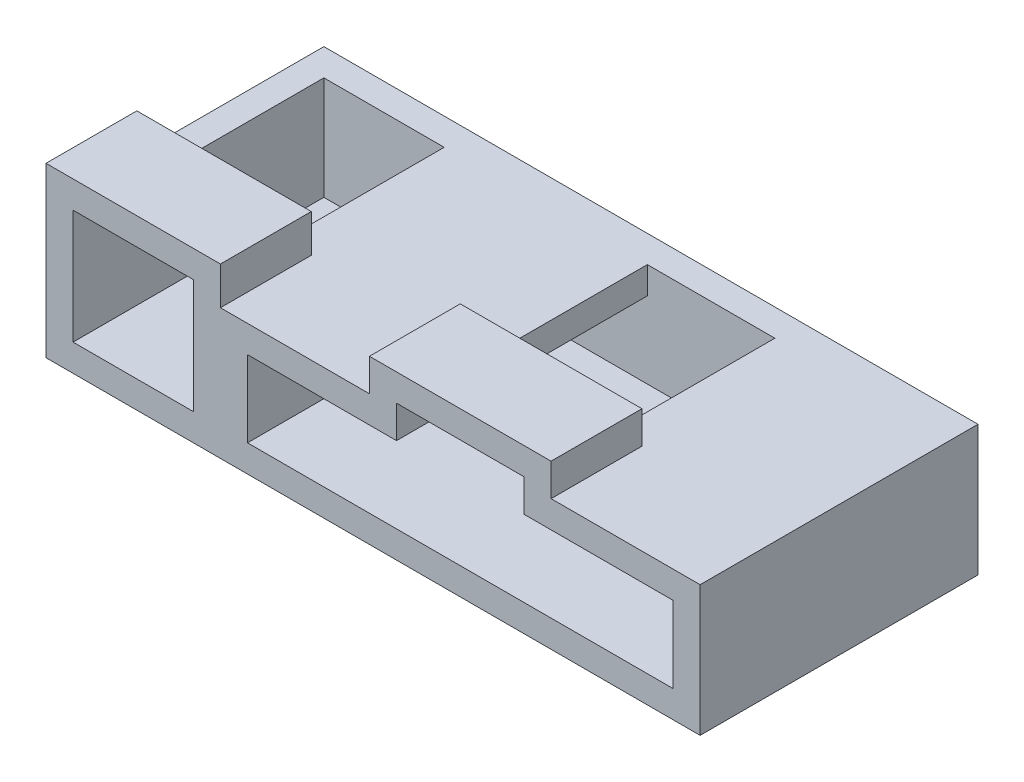
SolidWorks part; units mm, degrees
ref_plane "Front Plane" through (0, 0, 0) normal (0, 0, 1) x (1, 0, 0)
ref_plane "Top Plane" through (0, 0, 0) normal (0, 1, 0) x (1, 0, 0)
ref_plane "Right Plane" through (0, 0, 0) normal (1, 0, 0) x (0, 0, -1)
sketch "Sketch1" plane through (0, 0, 0) normal (0, 1, 0) x (1, 0, 0)
  line L1 (-43.6495, 20.2828) -> (-16.027, 20.2828)
  line L2 (-43.6495, 20.2828) -> (-43.6495, 32.0176)
  line L3 (-43.6495, 32.0176) -> (-16.027, 32.0176)
  line L4 (-16.027, 20.2828) -> (-16.027, 32.0176)
  dimension "D1" = 27.6225
  dimension "D2" = 11.7348
extrude "Boss-Extrude1" add sketch "Sketch1" along normal blind 7.112
sketch "Sketch2" plane through (0, 0, -20.2828) normal (0, 0, 1) x (1, 0, 0)
  line L0 (-36.2835, 7.112) -> (-36.2835, 5.5118)
  line L1 (-43.6495, 7.112) -> (-16.027, 7.112) construction
  line L2 (-36.2835, 5.5118) -> (-29.9906, 5.5118)
  line L3 (-29.9906, 5.5118) -> (-29.9906, 6.8834)
  line L4 (-29.9906, 6.8834) -> (-22.3198, 6.8834)
  line L5 (-22.3198, 6.8834) -> (-22.3198, 5.5118)
  line L6 (-22.3198, 5.5118) -> (-16.027, 5.5118)
  line L7 (-16.027, 7.112) -> (-16.027, 0) construction
  line L8 (-43.6495, 7.112) -> (-43.6495, 0) construction
  dimension "D1" = 7.366
  dimension "D2" = 1.6002
  dimension "D3" = 7.6708
  dimension "D4" = 1.3716
extrude "Cut-Extrude1" cut sketch "Sketch2" along direction (0, 0, -1) on the side against the normal through all and the other way through all
sketch "Sketch3" plane through (0, 0, -20.2828) normal (0, 0, 1) x (1, 0, 0)
  line L0 (-43.6495, 7.112) -> (-36.2835, 7.112) construction
  line L1 (-36.2835, 7.112) -> (-36.2835, 0) construction
  line L2 (-43.6495, 0) -> (-16.027, 0) construction
  line L3 (-36.2835, 0) -> (-43.6495, 0) construction
  line L4 (-43.6495, 0) -> (-43.6495, 7.112) construction
  line L5 (-42.5065, 5.969) -> (-37.4265, 5.969)
  line L6 (-37.4265, 5.969) -> (-37.4265, 1.143)
  line L7 (-37.4265, 1.143) -> (-42.5065, 1.143)
  line L8 (-42.5065, 1.143) -> (-42.5065, 5.969)
  line L9 (-36.2835, 5.5118) -> (-36.2835, 0) construction
  line L10 (-36.2835, 0) -> (-16.027, 0) construction
  line L11 (-16.027, 0) -> (-16.027, 5.5118) construction
  line L12 (-22.3198, 5.5118) -> (-16.027, 5.5118) construction
  line L13 (-16.027, 5.5118) -> (-16.027, 0) construction
  line L14 (-16.027, 5.5118) -> (-22.3198, 5.5118) construction
  line L15 (-22.3198, 5.5118) -> (-22.3198, 6.8834) construction
  line L16 (-22.3198, 6.8834) -> (-29.9906, 6.8834) construction
  line L17 (-29.9906, 6.8834) -> (-29.9906, 5.5118) construction
  line L18 (-29.9906, 5.5118) -> (-36.2835, 5.5118) construction
  line L19 (-35.1405, 4.3688) -> (-35.1405, 1.143)
  line L20 (-35.1405, 1.143) -> (-17.17, 1.143)
  line L21 (-17.17, 1.143) -> (-17.17, 4.3688)
  line L22 (-17.17, 4.3688) -> (-23.4628, 4.3688)
  line L23 (-23.4628, 4.3688) -> (-23.4628, 5.7404)
  line L24 (-23.4628, 5.7404) -> (-28.8476, 5.7404)
  line L25 (-28.8476, 5.7404) -> (-28.8476, 4.3688)
  line L26 (-28.8476, 4.3688) -> (-35.1405, 4.3688)
  dimension "D1" = 1.143
  dimension "D2" = 1.143
extrude "Cut-Extrude2" cut sketch "Sketch3" against normal offset from surface (10.5918 mm away) 1.143 up to face at (-29.6541, 5.0038, -32.0176)
sketch "Sketch4" plane through (0, 7.112, 0) normal (0, 1, 0) x (1, 0, 0)
  line L0 (-22.3198, 20.2828) -> (-22.3198, 32.0176) construction
  line L1 (-43.6495, 32.0176) -> (-22.3198, 32.0176)
  line L2 (-43.6495, 32.0176) -> (-43.6495, 24.1182)
  line L3 (-43.6495, 24.1182) -> (-22.3198, 24.1182)
  line L4 (-22.3198, 32.0176) -> (-22.3198, 24.1182)
  line L5 (-43.6495, 20.2828) -> (-36.2835, 20.2828) construction
  dimension "D1" = 3.8354
extrude "Cut-Extrude3" cut sketch "Sketch4" against normal up to surface (1.6002 mm away) up to face at (-33.137, 5.5118, -26.1502)
